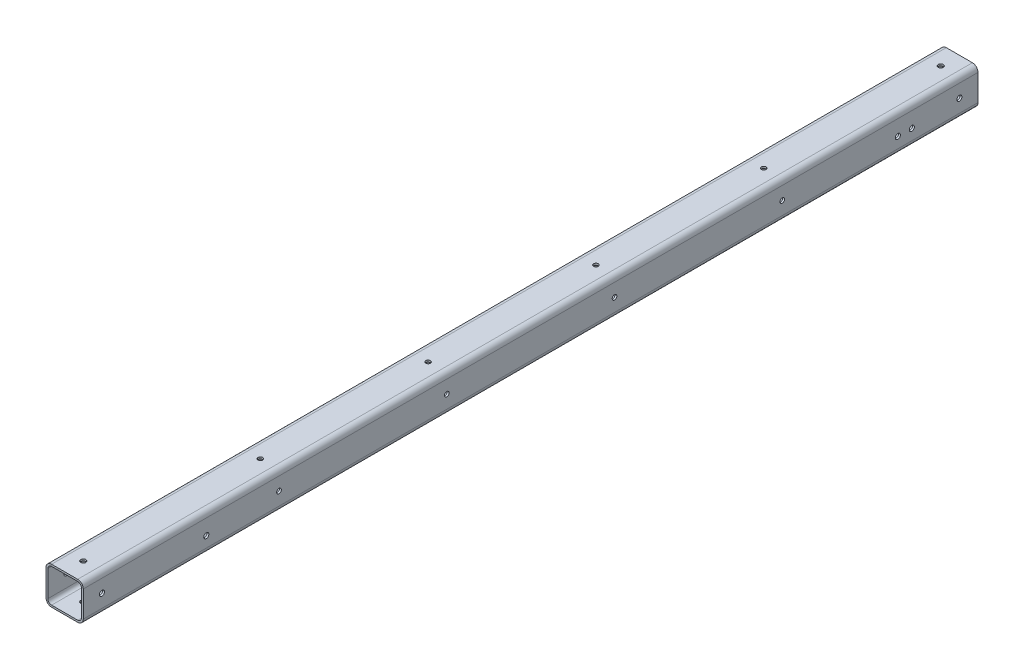
SolidWorks part; units mm, degrees
material "1.0038 (S235JRG2)"
ref_plane "Ebene vorne" through (0, 0, 0) normal (0, 0, 1) x (1, 0, 0)
ref_plane "Ebene oben" through (0, 0, 0) normal (0, 1, 0) x (1, 0, 0)
ref_plane "Ebene rechts" through (0, 0, 0) normal (1, 0, 0) x (0, 0, -1)
sketch "Skizze1" plane through (0, 0, 0) normal (0, 0, 1) x (1, 0, 0)
  line L0 (0, 0) -> (0, 67.8952) construction
  line L1 (-14, 20) -> (14, 20)
  line L2 (0, 0) -> (65.406, 0) construction
  line L3 (20, 14) -> (20, -14)
  line L4 (-20, 14) -> (-20, -14)
  line L5 (-14, -20) -> (14, -20)
  line L6 (-18, 14) -> (-18, -14)
  line L7 (-14, -18) -> (14, -18)
  line L8 (18, 14) -> (18, -14)
  line L9 (-14, 18) -> (14, 18)
  arc A0 (14, 20) -> (20, 14) centre (14, 14) cw
  arc A1 (-14, 20) -> (-20, 14) centre (-14, 14) ccw
  arc A2 (-14, -20) -> (-20, -14) centre (-14, -14) cw
  arc A3 (14, -20) -> (20, -14) centre (14, -14) ccw
  arc A4 (-14, -18) -> (-18, -14) centre (-14, -14) cw
  arc A5 (14, -18) -> (18, -14) centre (14, -14) ccw
  arc A6 (14, 18) -> (18, 14) centre (14, 14) cw
  arc A7 (-14, 18) -> (-18, 14) centre (-14, 14) ccw
  point P12 (20, 0)
  point P13 (0, 20)
  point P19 (-20, 0)
  dimension "D1" = 6
  dimension "D3" = 40
  dimension "D4" = 40
  dimension "D2" = 2
extrude "Aufsatz-Linear austragen1" add sketch "Skizze1" along normal mid plane 960
sketch "Skizze2" plane through (0, 20, 0) normal (0, 1, 0) x (1, 0, 0)
  line L0 (0, 0) -> (0, 498.4171) construction
  line L1 (14, 480) -> (-14, 480) construction
  line L2 (0, 0) -> (132.531, 0) construction
  circle A0 centre (0, 460) radius 2.75
  circle A1 centre (0, -460) radius 2.75
  dimension "D1" = 20
  dimension "D2" = 5.5
extrude "Schnitt-Linear austragen1" cut sketch "Skizze2" against normal blind 100
sketch "Skizze3" plane through (20, 0, 0) normal (1, 0, 0) x (0, 0, -1)
  line L0 (0, 0) -> (0, 141.2331) construction
  line L1 (0, 0) -> (517.4064, 0) construction
  line L2 (480, -14) -> (480, 14) construction
  circle A0 centre (460, 0) radius 2.75
  circle A1 centre (-460, 0) radius 2.75
  dimension "D1" = 20
  dimension "D2" = 5.5
extrude "Schnitt-Linear austragen2" cut sketch "Skizze3" against normal blind 100
sketch "Skizze4" plane through (20, 0, 0) normal (1, 0, 0) x (0, 0, -1)
  line L0 (409, -2.5) -> (394, -2.5) construction
  line L1 (480, -14) -> (480, 14) construction
  line L2 (-480, -20) -> (480, -20) construction
  line L3 (394, -2.5) -> (-348, -2.5) construction
  circle A0 centre (409, -2.5) radius 2.75
  circle A1 centre (394, -2.5) radius 2.75
  circle A2 centre (-348, -2.5) radius 2.75
  dimension "D2" = 5.5
  dimension "D1" = 15
  dimension "D3" = 71
  dimension "D4" = 17.5
  dimension "D5" = 742
extrude "Schnitt-Linear austragen3" cut sketch "Skizze4" against normal blind 10
sketch "Skizze5" plane through (0, 20, 0) normal (0, 1, 0) x (1, 0, 0)
  line L0 (0, 498.4171) -> (0, -514.6635) construction
  line L1 (0, 0) -> (127.6505, 0) construction
  line L2 (14, 480) -> (-14, 480) construction
  circle A0 centre (0, 270) radius 2.5
  circle A1 centre (0, 90) radius 2.5
  circle A5 centre (0, -270) radius 2.5
  circle A6 centre (0, -90) radius 2.5
  dimension "D1" = 5
  dimension "D3" = 180
  dimension "D2" = 210
extrude "Schnitt-Linear austragen4" cut sketch "Skizze5" against normal blind 60
sketch "Skizze6" plane through (-20, 0, 0) normal (-1, 0, 0) x (0, 0, 1)
  line L0 (0, 0) -> (503.9557, 0) construction
  line L1 (480, 14) -> (480, -14) construction
  line L2 (0, 0) -> (0, 112.6234) construction
  circle A0 centre (270, 0) radius 2.5
  circle A1 centre (90, 0) radius 2.5
  circle A2 centre (-270, 0) radius 2.5
  circle A3 centre (-90, 0) radius 2.5
  dimension "D1" = 210
  dimension "D2" = 180
  dimension "D3" = 5
extrude "Schnitt-Linear austragen5" cut sketch "Skizze6" against normal blind 100
